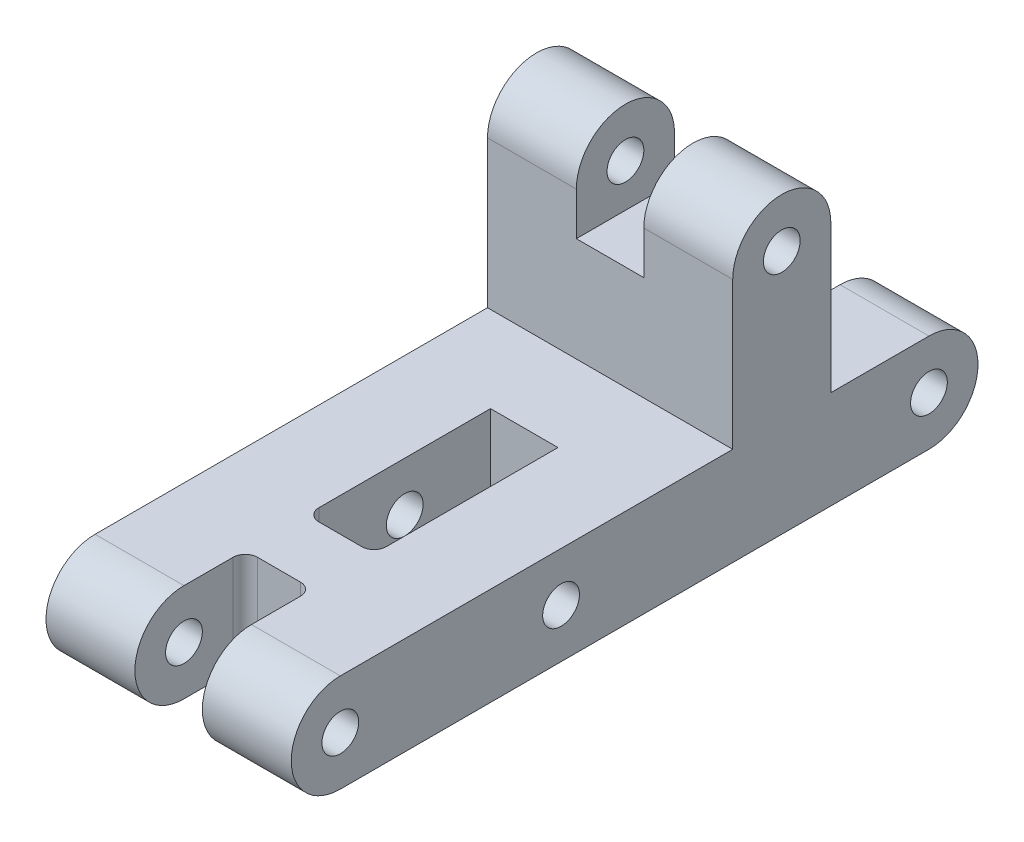
SolidWorks part; units mm, degrees
ref_plane "Alzado" through (0, 0, 0) normal (0, 0, 1) x (1, 0, 0)
ref_plane "Planta" through (0, 0, 0) normal (0, 1, 0) x (1, 0, 0)
ref_plane "Vista lateral" through (0, 0, 0) normal (1, 0, 0) x (0, 0, -1)
sketch "Croquis1" plane through (0, 0, 0) normal (1, 0, 0) x (0, 0, -1)
  line L0 (-15, 0) -> (15, 0) construction
  line L1 (-15, 4) -> (-1, 4)
  line L2 (-15, -4) -> (15, -4)
  line L3 (7, 4) -> (15, 4)
  line L5 (-1, 4) -> (-1, 16)
  line L6 (-1, 16) -> (7, 16) construction
  line L7 (7, 4) -> (7, 16)
  line L8 (-15, 4) -> (-33, 4)
  line L9 (-15, -4) -> (-33, -4)
  line L10 (-33, 4) -> (-33, -4) construction
  arc A0 (-15, 4) -> (-15, -4) centre (-15, 0) ccw construction
  arc A1 (15, -4) -> (15, 4) centre (15, 0) ccw
  circle A2 centre (15, 0) radius 1.5
  arc A3 (7, 16) -> (-1, 16) centre (3, 16) ccw
  circle A4 centre (3, 16) radius 1.5
  circle A5 centre (-15, 0) radius 1.5
  arc A6 (-33, 4) -> (-33, -4) centre (-33, 0) ccw
  circle A7 centre (-33, 0) radius 1.5
  point P3 (0, 0)
  dimension "D2" = 4
  dimension "D3" = 3
  dimension "D4" = 4
  dimension "D7" = 18
  dimension "D1" = 30
  dimension "D5" = 8
  dimension "D6" = 12
extrude "Saliente-Extruir1" add sketch "Croquis1" along normal mid plane 20
sketch "Croquis2" plane through (0, 0, 0) normal (1, 0, 0) x (0, 0, -1)
  line L0 (-1, 16) -> (-1, 4) construction
  line L1 (-1, 12.5) -> (7, 12.5)
  line L2 (-1, 12.5) -> (-1, 20)
  line L3 (-1, 20) -> (7, 20)
  line L4 (7, 12.5) -> (7, 20)
  line L5 (7, 4) -> (7, 16) construction
  line L6 (-1, 4) -> (-33, 4) construction
  line L7 (-8, 4) -> (-23, 4)
  line L8 (-8, 4) -> (-8, -4)
  line L9 (-8, -4) -> (-23, -4)
  line L10 (-23, 4) -> (-23, -4)
  line L11 (-33, -4) -> (15, -4) construction
  line L12 (15, 4) -> (7, 4) construction
  line L13 (10, 4) -> (19, 4)
  line L14 (10, 4) -> (10, -4)
  line L15 (10, -4) -> (19, -4)
  line L16 (19, 4) -> (19, -4)
  line L17 (-1, 4) -> (-33, 4) construction
  line L18 (-28, 4) -> (-37, 4)
  line L19 (-28, 4) -> (-28, -4)
  line L20 (-28, -4) -> (-37, -4)
  line L21 (-37, 4) -> (-37, -4)
  line L22 (-33, -4) -> (15, -4) construction
  arc A0 (7, 16) -> (-1, 16) centre (3, 16) ccw construction
  arc A2 (15, -4) -> (15, 4) centre (15, 0) ccw construction
  circle A4 centre (-15, 0) radius 1.5 construction
  arc A5 (-33, 4) -> (-33, -4) centre (-33, 0) ccw construction
  dimension "D5" = 9
  dimension "D1" = 7.5
  dimension "D2" = 8
  dimension "D3" = 9
  dimension "D4" = 8
extrude "Cortar-Extruir1" cut sketch "Croquis2" against normal mid plane 5.5
fillet "Redondeo1" radius 1 6 edges at (2.75, 0, 23) (-2.75, 0, 23) (2.75, 0, 28) (-2.75, 0, 28) (2.75, 0, -10) (-2.75, 0, -10)
